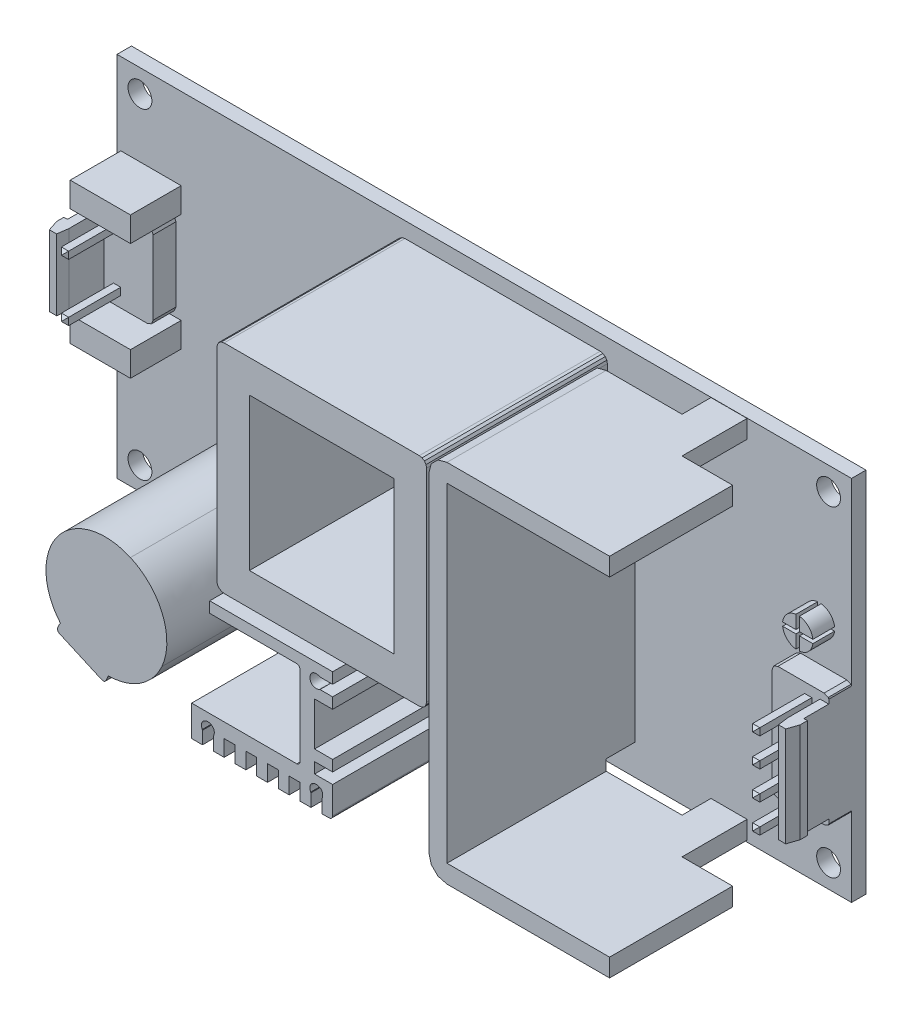
SolidWorks part; units mm, degrees
ref_plane "Спереди" through (0, 0, 0) normal (0, 0, 1) x (1, 0, 0)
ref_plane "Сверху" through (0, 0, 0) normal (0, 1, 0) x (1, 0, 0)
ref_plane "Справа" through (0, 0, 0) normal (1, 0, 0) x (0, 0, -1)
sketch "Model" plane through (0, 0, 0) normal (0, 0, 1) x (1, 0, 0)
  line L3 (0, 50.8) -> (101.6, 50.8)
  line L4 (0, 50.8) -> (0, 0)
  line L7 (0, 0) -> (101.6, 0)
  line L8 (101.6, 50.8) -> (101.6, 0)
  circle A8 centre (98.425, 3.175) radius 1.65
  circle A14 centre (3.175, 47.625) radius 1.65
  circle A15 centre (3.175, 3.175) radius 1.65
  circle A18 centre (98.425, 47.625) radius 1.65
  dimension "D1" = 101.6
  dimension "D3" = 95.25
  dimension "D4" = 3.175
  dimension "D5" = 3.175
  dimension "D6" = 44.45
  dimension "D7" = 3.3
  dimension "D2" = 50.8
extrude "текстолит" add sketch "Model" against normal blind 2
sketch "Sketch2" plane through (0, 0, 0) normal (0, 0, 1) x (1, 0, 0)
  line L0 (95.0704, 31.3331) -> (96.9053, 31.3331)
  line L1 (96.9053, 31.3331) -> (96.9053, 29.5015)
  line L2 (95.0694, 31.8447) -> (96.9053, 31.8447)
  line L3 (96.9053, 31.8447) -> (96.9053, 33.6845)
  line L4 (97.3925, 33.6874) -> (97.3925, 31.8447)
  line L5 (97.3925, 31.8447) -> (99.2535, 31.8447)
  line L6 (97.3925, 29.4986) -> (97.3925, 31.3331)
  line L7 (97.3925, 31.3331) -> (99.2525, 31.3331)
  arc A0 (95.0704, 31.3331) -> (96.9053, 29.5015) centre (97.1614, 31.593) ccw
  arc A1 (99.2535, 31.8447) -> (97.3925, 33.6874) centre (97.1614, 31.593) ccw
  arc A2 (96.9053, 33.6845) -> (95.0694, 31.8447) centre (97.1614, 31.593) ccw
  arc A3 (97.3925, 29.4986) -> (99.2525, 31.3331) centre (97.1614, 31.593) ccw
sketch "Sketch3" plane through (0, 0, 0) normal (0, 0, 1) x (1, 0, 0)
  line L22 (0.5362, 39.5062) -> (8.8733, 39.5062)
  line L23 (8.8733, 39.5062) -> (8.8733, 36.0718)
  line L24 (8.8733, 36.0718) -> (0.5362, 36.0718)
  line L25 (0.5362, 36.0718) -> (0.5362, 39.5062)
  line L26 (0.5362, 23.3673) -> (8.8733, 23.3673)
  line L27 (8.8733, 23.3673) -> (8.8733, 19.9329)
  line L28 (8.8733, 19.9329) -> (0.5362, 19.9329)
  line L29 (0.5362, 19.9329) -> (0.5362, 23.3673)
sketch "Sketch4" plane through (0, 0, 0) normal (0, 0, 1) x (1, 0, 0)
  line L0 (18.0243, 4.5158) -> (17.8181, 4.0531)
  line L1 (18.0526, 3.4424) -> (23.9027, 0.8378)
  line L2 (24.5128, 1.0733) -> (24.7181, 1.5353)
  arc A0 (24.7564, 1.7605) -> (32.2111, 6.5675) centre (24.7615, 9.9365) ccw
  arc A2 (24.7181, 1.5353) -> (24.7564, 1.7605) centre (24.3052, 1.7214) ccw
  arc A4 (16.8723, 13.3967) -> (18.2122, 4.7257) centre (24.3565, 10.1142) ccw
  arc A5 (18.2122, 4.7257) -> (18.0243, 4.5158) centre (18.44, 4.3327) ccw
  arc A8 (23.9027, 0.8378) -> (24.5128, 1.0733) centre (24.0897, 1.2613) ccw
  arc A10 (17.8181, 4.0531) -> (18.0526, 3.4424) centre (18.2405, 3.8649) ccw
  spline S0 degree 3 poles (16.8723, 13.3967) (18.7111, 17.5272) (23.6356, 19.346) (27.8713, 17.4603) knots 0 0 0 0 1 1 1 1
  spline S1 degree 3 poles (27.8713, 17.4603) (32.1075, 15.5745) (34.0499, 10.6975) (32.2111, 6.5675) knots 0 0 0 0 1 1 1 1
  point P4 (0, 0)
sketch "Sketch5" plane through (0, 0, 0) normal (0, 0, 1) x (1, 0, 0)
  line L0 (38.8335, 17.7631) -> (55.8344, 17.7631)
  line L1 (55.8344, 17.7631) -> (55.8344, 16.2608)
  line L2 (55.8344, 16.2608) -> (54.0819, 16.2608)
  line L3 (54.0819, 14.7585) -> (55.8344, 14.7585)
  line L4 (55.8344, 14.7585) -> (55.8344, 13.2624)
  line L5 (55.8344, 13.2624) -> (53.3338, 13.2624)
  line L6 (53.3338, 13.2624) -> (53.3338, 7.2589)
  line L7 (53.3338, 7.2589) -> (55.8344, 7.2589)
  line L8 (55.8344, 7.2589) -> (55.8344, 5.7561)
  line L9 (55.8344, 5.7561) -> (53.3338, 5.7561)
  line L10 (53.3338, 5.7561) -> (53.3338, 4.26)
  line L11 (53.3338, 4.26) -> (55.8344, 4.26)
  line L12 (55.8344, 4.26) -> (55.8344, 0.5074)
  line L13 (55.8344, 0.5074) -> (55.8282, 0.4538)
  line L14 (55.335, 0.0085) -> (55.3891, 0.0085)
  line L15 (49.8304, 0.0085) -> (48.3342, 0.0085)
  line L16 (48.3342, 0.0085) -> (48.3342, 2.2588)
  line L17 (48.3342, 2.2588) -> (46.832, 2.2588)
  line L18 (46.832, 2.2588) -> (46.832, 0.0085)
  line L19 (46.832, 0.0085) -> (45.3358, 0.0085)
  line L20 (45.3358, 0.0085) -> (45.3358, 2.2588)
  line L21 (45.3358, 2.2588) -> (43.833, 2.2588)
  line L22 (43.833, 2.2588) -> (43.833, 0.0085)
  line L23 (43.833, 0.0085) -> (42.3313, 0.0085)
  line L24 (42.3313, 0.0085) -> (42.3313, 2.2588)
  line L25 (42.3313, 2.2588) -> (40.8346, 2.2588)
  line L26 (40.8346, 2.2588) -> (40.8346, 0.0085)
  line L27 (40.8346, 0.0085) -> (39.3318, 0.0085)
  line L28 (37.7938, 1.8258) -> (37.8357, 1.7605)
  line L29 (37.8357, 1.7605) -> (37.8357, 0.0085)
  line L30 (37.8357, 0.0085) -> (36.3334, 0.0085)
  line L31 (36.3334, 0.0085) -> (36.3334, 4.26)
  line L32 (36.3334, 4.26) -> (50.8343, 4.26)
  line L33 (50.8343, 4.26) -> (50.8874, 4.26)
  line L34 (51.3327, 4.6997) -> (51.3327, 4.7589)
  line L35 (51.3327, 4.7589) -> (51.3327, 15.7624)
  line L36 (51.3327, 15.7624) -> (51.3327, 15.8155)
  line L37 (50.8874, 16.2552) -> (50.8343, 16.2608)
  line L38 (50.8343, 16.2608) -> (38.8335, 16.2608)
  line L39 (38.8335, 16.2608) -> (38.8335, 17.7631)
  line L40 (39.3318, 0.0085) -> (39.3318, 1.7605)
  line L41 (39.3318, 1.7605) -> (39.3732, 1.8258)
  line L42 (52.8354, 0.0085) -> (51.3327, 0.0085)
  line L43 (51.3327, 0.0085) -> (51.3327, 2.2588)
  line L44 (51.3327, 2.2588) -> (49.8304, 2.2588)
  line L45 (49.8304, 2.2588) -> (49.8304, 0.0085)
  line L46 (55.335, 0.0085) -> (54.3316, 0.0085)
  line L47 (54.3316, 0.0085) -> (54.3316, 1.7605)
  line L48 (54.3316, 1.7605) -> (54.3729, 1.8258)
  line L49 (52.7936, 1.8258) -> (52.8354, 1.7605)
  line L50 (52.8354, 1.7605) -> (52.8354, 0.0085)
  line L51 (54.0819, 16.2608) -> (54.0104, 16.3027)
  line L52 (54.0104, 14.7172) -> (54.0819, 14.7585)
  spline S0 degree 3 poles (55.3891, 0.0085) (55.6107, 0.0391) (55.815, 0.224) (55.8282, 0.4538) knots 0 0 0 0 1 1 1 1
  spline S1 degree 3 poles (50.8874, 4.26) (51.1223, 4.2891) (51.2984, 4.4658) (51.3327, 4.6997) knots 0 0 0 0 1 1 1 1
  spline S2 degree 3 poles (51.3327, 15.8155) (51.3061, 16.0392) (51.1172, 16.2424) (50.8874, 16.2552) knots 0 0 0 0 1 1 1 1
  spline S3 degree 3 poles (39.3732, 1.8258) (40.0258, 3.5844) (37.1387, 3.5788) (37.7938, 1.8258) knots 0 0 0 0 1 1 1 1
  spline S4 degree 3 poles (54.3729, 1.8258) (55.024, 3.5829) (52.1379, 3.5809) (52.7936, 1.8258) knots 0 0 0 0 1 1 1 1
  spline S5 degree 3 poles (54.0104, 16.3027) (52.2646, 16.9543) (52.2651, 14.0707) (54.0104, 14.7172) knots 0 0 0 0 1 1 1 1
sketch "Sketch6" plane through (0, 0, 0) normal (0, 0, 1) x (1, 0, 0)
  line L0 (38.833, 47.6574) -> (38.833, 19.6289)
  line L1 (38.833, 19.6289) -> (38.8963, 19.2419)
  line L2 (38.8963, 19.2419) -> (39.1204, 18.9197)
  line L3 (39.1204, 18.9197) -> (39.4207, 18.7435)
  line L4 (39.4207, 18.7435) -> (39.8297, 18.6322)
  line L5 (39.8297, 18.6322) -> (41.861, 18.6322)
  line L6 (41.861, 18.6322) -> (66.8323, 18.6322)
  line L7 (39.8292, 48.6523) -> (66.8323, 48.6523)
  line L8 (63.3253, 23.1359) -> (63.3253, 44.1504)
  line L9 (63.3253, 44.1504) -> (43.327, 44.1504)
  line L10 (43.327, 44.1504) -> (43.327, 23.1359)
  line L11 (43.327, 23.1359) -> (63.3253, 23.1359)
  line L12 (39.8292, 48.6523) -> (39.4309, 48.5541)
  line L13 (39.4309, 48.5541) -> (39.1199, 48.3667)
  line L14 (39.1199, 48.3667) -> (38.9177, 48.0123)
  line L15 (38.9177, 48.0123) -> (38.833, 47.6574)
  line L16 (66.8323, 18.6322) -> (67.2301, 18.7277)
  line L17 (67.2301, 18.7277) -> (67.5319, 18.9197)
  line L18 (67.5319, 18.9197) -> (67.7448, 19.2419)
  line L19 (67.7448, 19.2419) -> (67.8291, 19.6289)
  line L20 (67.8291, 19.6289) -> (67.8291, 47.6574)
  line L21 (67.8291, 47.6574) -> (67.7535, 48.0414)
  line L22 (67.7535, 48.0414) -> (67.5319, 48.3667)
  line L23 (67.5319, 48.3667) -> (67.1969, 48.5689)
  line L24 (67.1969, 48.5689) -> (66.8323, 48.6523)
sketch "Sketch7" plane through (0, 0, 0) normal (0, 0, 1) x (1, 0, 0)
  line L0 (71.6598, 48.2676) -> (71.6598, 2.7439)
  line L1 (94.1541, 50.7671) -> (71.6598, 50.7671)
  line L3 (71.6598, 0.2434) -> (70.4098, 0.5763)
  line L4 (70.4098, 0.5763) -> (69.4927, 1.4934)
  line L5 (69.4927, 1.4934) -> (69.1598, 2.7434)
  line L8 (94.1541, 0.2434) -> (71.6598, 0.2434)
  line L9 (71.6598, 50.7671) -> (70.4098, 50.4347)
  line L10 (70.4098, 50.4347) -> (69.4922, 49.5176)
  line L11 (69.4922, 49.5176) -> (69.1598, 48.2676)
  line L12 (69.1598, 48.2676) -> (69.1598, 2.7434)
  line L13 (94.1541, 0.2434) -> (94.1541, 2.7439)
  line L14 (94.1541, 2.7439) -> (71.6598, 2.7439)
  line L15 (71.6598, 48.2676) -> (94.1541, 48.2676)
  line L16 (94.1541, 48.2676) -> (94.1541, 50.7671)
sketch "Sketch8" plane through (0, 0, 0) normal (0, 0, 1) x (1, 0, 0)
  line L0 (94.56, 10.5693) -> (100.9567, 10.5693)
  line L1 (100.9567, 10.5693) -> (101.525, 10.8047)
  line L2 (101.525, 10.8047) -> (101.6, 10.9858)
  line L3 (101.6, 10.9858) -> (101.6, 25.9257)
  line L4 (101.6, 25.9257) -> (101.525, 26.1068)
  line L5 (101.525, 26.1068) -> (100.9567, 26.3422)
  line L6 (100.9567, 26.3422) -> (94.56, 26.3422)
  line L7 (94.56, 26.3422) -> (93.9917, 26.1068)
  line L8 (93.9917, 26.1068) -> (93.7563, 25.5384)
  line L9 (93.7563, 25.5384) -> (93.7563, 11.3731)
  line L10 (93.7563, 11.3731) -> (93.9917, 10.8047)
  line L11 (93.9917, 10.8047) -> (94.56, 10.5693)
  line L12 (101.6, 0) -> (101.6, 50.8) construction
extrude "подстройка напряжения" add sketch "Sketch2" along normal blind 3
sketch "Sketch9" plane through (0, 0, 0) normal (0, 0, 1) x (1, 0, 0)
  line L0 (98.2611, 12.0619) -> (99.2595, 12.0619)
  line L1 (99.2595, 12.0619) -> (99.2595, 13.0603)
  line L2 (99.2595, 13.0603) -> (98.2611, 13.0603)
  line L3 (98.2611, 13.0603) -> (98.2611, 12.0619)
  line L4 (98.2611, 23.9463) -> (99.2595, 23.9463)
  line L5 (99.2595, 23.9463) -> (99.2595, 24.9447)
  line L6 (99.2595, 24.9447) -> (98.2611, 24.9447)
  line L7 (98.2611, 24.9447) -> (98.2611, 23.9463)
  line L8 (98.2611, 19.9848) -> (99.2595, 19.9848)
  line L9 (99.2595, 19.9848) -> (99.2595, 20.9834)
  line L10 (99.2595, 20.9834) -> (98.2611, 20.9834)
  line L11 (98.2611, 16.0239) -> (99.2595, 16.0239)
  line L12 (99.2595, 16.0239) -> (99.2595, 17.0222)
  line L13 (99.2595, 17.0222) -> (98.2611, 17.0222)
  line L14 (98.2611, 17.0222) -> (98.2611, 16.0239)
  line L15 (98.2611, 13.0602) -> (99.2593, 13.0602)
  line L16 (99.2593, 13.0602) -> (99.2593, 12.0619)
  line L17 (98.2611, 24.9446) -> (99.2593, 24.9446)
  line L18 (99.2593, 24.9446) -> (99.2593, 23.9463)
  line L19 (98.2611, 20.9836) -> (98.2611, 19.9848)
  line L20 (98.2611, 20.9836) -> (99.2593, 20.9836)
  line L21 (99.2593, 20.9836) -> (99.2593, 19.9848)
  line L22 (99.2593, 17.0222) -> (99.2593, 16.0239)
extrude "CN2 вывод разъем" add sketch "Sketch8" along normal blind 3.15
extrude "CN2 вывод контакты" add sketch "Sketch9" along normal blind 10.8
chamfer "CN2 вывод контакты-45гр" distance 0.45 angle 45 16 edges at (98.7602, 24.9446, 10.8) (99.2593, 24.4454, 10.8) (98.2611, 24.4454, 10.8) (98.7602, 23.9463, 10.8) (98.7602, 20.9834, 10.8) (99.2593, 20.4841, 10.8) (98.2611, 20.4841, 10.8) (98.7602, 19.9848, 10.8) (98.7603, 17.0222, 10.8) (99.2595, 16.5231, 10.8) (98.2611, 16.5231, 10.8) (98.7603, 16.0239, 10.8) (98.7602, 13.0602, 10.8) (99.2593, 12.5611, 10.8) (98.7602, 12.0619, 10.8) (98.2611, 12.5611, 10.8)
sketch "Sketch11" plane through (0, 10.5693, 0) normal (0, -1, 0) x (1, 0, 0)
  line L0 (94.56, 3.15) -> (100.9567, 3.15) construction
  line L1 (100.4, 3.15) -> (101.6, 3.15)
  line L2 (100.4, 3.15) -> (100.4, 7.6)
  line L3 (100.6, 9.1) -> (101.6, 9.1)
  line L4 (101.6, 3.15) -> (101.6, 6.6)
  line L5 (0, -2) -> (101.6, -2) construction
  line L6 (101.6, -2) -> (101.6, 0) construction
  line L7 (101.6, 6.6) -> (102.1, 6.6)
  line L8 (102.1, 6.6) -> (102.1, 7.6)
  line L9 (102.1, 7.6) -> (101.6, 9.1)
  line L10 (100.6, 9.1) -> (100.4, 7.6)
  dimension "D1" = 11.1
  dimension "D2" = 1.2
  dimension "D3" = 8.6
  dimension "D4" = 9.6
  dimension "D5" = 1.7
  dimension "D6" = 1.5
  dimension "D7" = 0.2
extrude "CN2 вывод разъем зацеп" add sketch "Sketch11" against normal blind 13.77 from offset 1 offset against normal yes
extrude "кожух мясо" add sketch "Sketch7" along normal blind 26.02
sketch "Sketch12" plane through (0, 0.2434, 0) normal (0, -1, 0) x (1, 0, 0)
  line L0 (0, 0) -> (101.6, 0) construction
  line L1 (94.1541, 0) -> (87.1541, 0)
  line L2 (94.1541, 0) -> (94.1541, 9)
  line L3 (94.1541, 9) -> (87.1541, 9)
  line L4 (87.1541, 0) -> (87.1541, 9)
  line L5 (82.1598, 0) -> (69.1598, 0)
  line L6 (82.1598, 0) -> (82.1598, 4)
  line L7 (82.1598, 4) -> (69.1598, 4)
  line L8 (69.1598, 0) -> (69.1598, 4)
  line L9 (69.1598, 26.02) -> (69.1598, 0) construction
  dimension "D1" = 7
  dimension "D2" = 9
  dimension "D3" = 4
  dimension "D4" = 13
extrude "кожух вырез лево" cut sketch "Sketch12" against normal blind 4
sketch "Sketch13" plane through (0, 50.7671, 0) normal (0, 1, 0) x (1, 0, 0)
  line L1 (94.1541, 0) -> (87.1541, 0)
  line L2 (94.1541, 0) -> (94.1541, -9)
  line L3 (94.1541, -9) -> (87.1541, -9)
  line L4 (87.1541, 0) -> (87.1541, -9)
  line L5 (82.1598, -4) -> (69.1598, -4)
  line L6 (82.1598, -4) -> (82.1598, 0)
  line L7 (82.1598, 0) -> (69.1598, 0)
  line L8 (69.1598, -4) -> (69.1598, 0)
  dimension "D1" = 4
  dimension "D2" = 13
  dimension "D3" = 9
  dimension "D4" = 7
extrude "кожух вырез право" cut sketch "Sketch13" against normal blind 4
sketch "Sketch14" plane through (0, 0, 0) normal (0, 0, 1) x (1, 0, 0)
  line L0 (0.1599, 34.621) -> (0.1599, 34.8242)
  line L1 (0.1599, 24.8154) -> (0.1599, 24.6122)
  line L4 (0.1599, 24.8154) -> (1.3613, 24.8154)
  line L5 (1.3613, 24.8154) -> (1.3613, 34.621)
  line L6 (1.3613, 34.621) -> (0.1599, 34.621)
  line L11 (7.3603, 23.8166) -> (7.9205, 24.052)
  line L12 (7.9205, 24.052) -> (8.1559, 24.6122)
  line L13 (8.1559, 24.6122) -> (8.1559, 34.8242)
  line L14 (8.1559, 34.8242) -> (7.9205, 35.3844)
  line L15 (7.9205, 35.3844) -> (7.3603, 35.6198)
  line L16 (7.3603, 35.6198) -> (0.9555, 35.6198)
  line L17 (0.9555, 35.6198) -> (0.3953, 35.3844)
  line L18 (0.3953, 35.3844) -> (0.1599, 34.8242)
  line L19 (0.1599, 24.6122) -> (0.3953, 24.052)
  line L20 (0.3953, 24.052) -> (0.9555, 23.8166)
  line L21 (0.9555, 23.8166) -> (7.3603, 23.8166)
extrude "предохранители fs1-fs2" add sketch "Sketch3" along normal blind 7.01
sketch "Sketch15" plane through (0, 0, 0) normal (0, 0, 1) x (1, 0, 0)
  line L0 (3.6587, 33.2331) -> (2.6603, 33.2331)
  line L1 (2.6603, 33.2331) -> (2.6603, 34.2316)
  line L2 (2.6603, 34.2316) -> (3.6587, 34.2316)
  line L3 (3.6587, 34.2316) -> (3.6587, 33.2331)
  line L4 (3.6587, 25.302) -> (2.6603, 25.302)
  line L5 (2.6603, 25.302) -> (2.6603, 26.3086)
  line L6 (2.6603, 26.3086) -> (3.6587, 26.3086)
  line L7 (3.6587, 26.3086) -> (3.6587, 25.302)
  line L8 (3.6582, 34.2314) -> (2.66, 34.2314)
  line L9 (2.66, 34.2314) -> (2.66, 33.2331)
  line L10 (3.6582, 26.3085) -> (2.66, 26.3085)
  line L11 (2.66, 26.3085) -> (2.66, 25.302)
extrude "CN1 вывод разъем" add sketch "Sketch14" along normal blind 3.15
extrude "CN1 вывод контакты" add sketch "Sketch15" along normal blind 10.8
chamfer "CN1 вывод контакты-45гр" distance 0.45 angle 45 8 edges at (3.1595, 25.302, 10.8) (3.6587, 25.8053, 10.8) (2.6603, 25.8053, 10.8) (3.1595, 26.3086, 10.8) (3.1595, 33.2331, 10.8) (3.6587, 33.7323, 10.8) (3.1595, 34.2316, 10.8) (2.6603, 33.7323, 10.8)
sketch "Sketch16" plane through (0, 24.8154, 0) normal (0, 1, 0) x (1, 0, 0)
  line L0 (0, 0) -> (101.6, 0) construction
  line L1 (0.1599, -3.15) -> (0.1599, 0) construction
  line L2 (1.3599, 0) -> (1.3599, -8.01)
  line L3 (1.1599, -9.51) -> (0.1599, -9.51)
  line L4 (0.1599, 0) -> (0.1599, -7.01)
  line L5 (1.3599, -8.01) -> (1.1599, -9.51)
  line L6 (0.1599, -9.51) -> (-0.3401, -8.01)
  line L7 (-0.3401, -8.01) -> (-0.3401, -7.01)
  line L8 (-0.3401, -7.01) -> (0.1599, -7.01)
  line L9 (1.3599, 0) -> (0.1599, 0)
  dimension "D1" = 1
  dimension "D2" = 9.51
  dimension "D3" = 7.01
  dimension "D4" = 1
  dimension "D5" = 1.7
  dimension "D6" = 1.5
  dimension "D7" = 0.5
  dimension "D8" = 0.5
extrude "CN1 вывод разъем зацеп" add sketch "Sketch16" along normal up to surface (9.8056 mm away) up to face at (0.7606, 34.621, 1.575)
extrude "радиатор" add sketch "Sketch5" along normal blind 26.01
sketch "Sketch17" plane through (0, 0.0085, 0) normal (0, -1, 0) x (1, 0, 0)
  line L0 (36.3334, 26.01) -> (36.3334, 0) construction
  line L1 (36.3334, 2) -> (37.5834, 2)
  line L2 (36.3334, 2) -> (36.3334, 0)
  line L3 (36.3334, 0) -> (37.5834, 0)
  line L4 (37.5834, 2) -> (37.5834, 0)
  line L5 (0, 0) -> (101.6, 0) construction
  line L6 (39.8292, 0) -> (66.8323, 0) construction
  line L7 (39.5834, 0) -> (41.8334, 0)
  line L8 (39.5834, 0) -> (39.5834, 2)
  line L9 (39.5834, 2) -> (41.8334, 2)
  line L10 (41.8334, 0) -> (41.8334, 2)
  line L11 (63.3253, 0) -> (43.327, 0) construction
  line L12 (42.6334, 0) -> (43.0834, 0)
  line L13 (42.6334, 0) -> (42.6334, 2)
  line L14 (42.6334, 2) -> (43.0834, 2)
  line L15 (43.0834, 0) -> (43.0834, 2)
  line L16 (46.1334, 0) -> (52.5834, 0)
  line L17 (46.1334, 0) -> (46.1334, 2)
  line L18 (46.1334, 2) -> (52.5834, 2)
  line L19 (52.5834, 0) -> (52.5834, 2)
  line L21 (54.5834, 0) -> (56.6334, 0)
  line L22 (54.5834, 0) -> (54.5834, 2)
  line L23 (54.5834, 2) -> (56.6334, 2)
  line L24 (56.6334, 0) -> (56.6334, 2)
  dimension "D1" = 2
  dimension "D2" = 1.25
  dimension "D3" = 2.25
  dimension "D4" = 2
  dimension "D5" = 0.8
  dimension "D6" = 0.45
  dimension "D7" = 3.05
  dimension "D8" = 6.45
  dimension "D9" = 2
  dimension "D10" = 2.05
extrude "радиатор-вырез" cut sketch "Sketch17" against normal up to surface (17.7546 mm away) up to face at (47.3339, 17.7631, 13.005)
extrude "конденсатор" add sketch "Sketch4" along normal blind 26.01
extrude "трансформатор" add sketch "Sketch6" along normal blind 25.01
